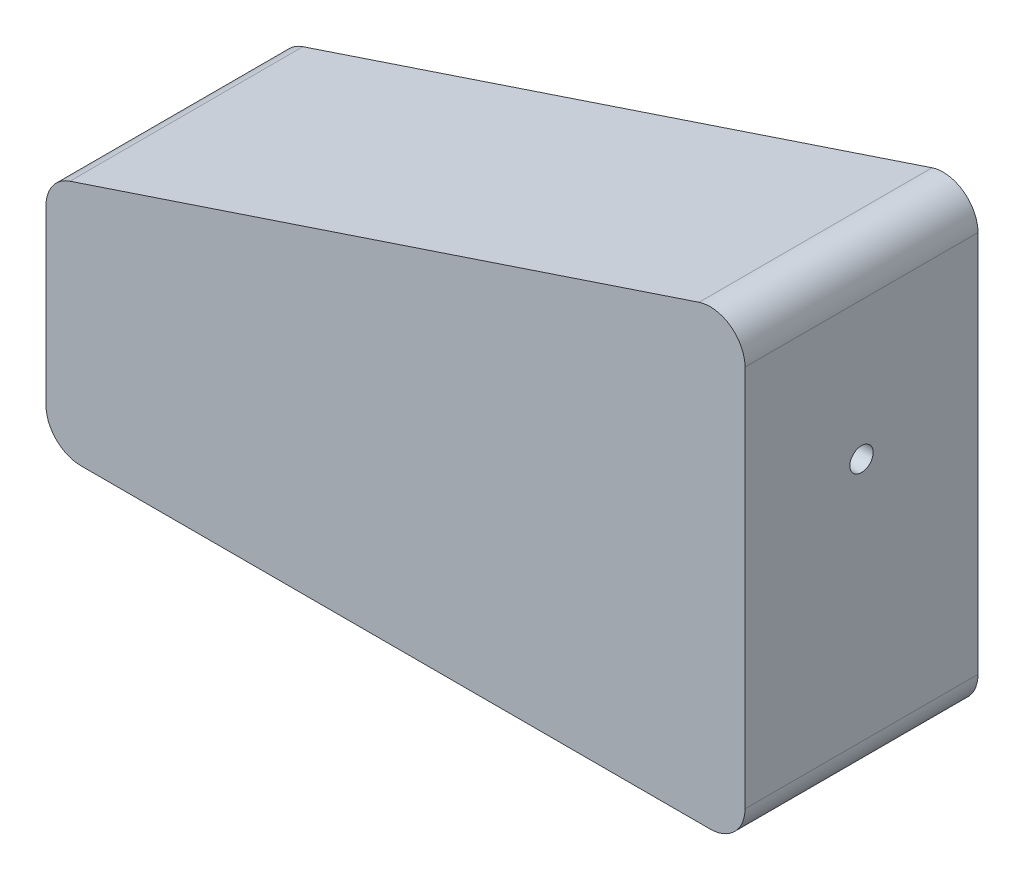
SolidWorks part; units mm, degrees
ref_plane "Plan de face" through (0, 0, 0) normal (0, 0, 1) x (1, 0, 0)
ref_plane "Plan de dessus" through (0, 0, 0) normal (0, 1, 0) x (1, 0, 0)
ref_plane "Plan de droite" through (0, 0, 0) normal (1, 0, 0) x (0, 0, -1)
sketch "Esquisse1" plane through (0, 0, 0) normal (0, 0, 1) x (1, 0, 0)
  line L0 (0, 0) -> (60, 0)
  line L1 (60, 0) -> (60, 40)
  line L2 (60, 40) -> (0, 20)
  line L3 (0, 20) -> (0, 0)
  dimension "D1" = 60
  dimension "D2" = 20
  dimension "D3" = 40
extrude "Boss.-Extru.1" add sketch "Esquisse1" along normal blind 20
fillet "Congé1" radius 3 4 edges at (0, 0, 10) (60, 0, 10) (60, 40, 10) (0, 20, 10)
sketch "Esquisse2" plane through (60, 0, 0) normal (1, 0, 0) x (0, 0, -1)
  line L0 (-10, 38.8377) -> (-10, 0) construction
  line L1 (0, 38.8377) -> (-20, 38.8377) construction
  line L2 (0, 0) -> (-20, 0) construction
  circle A0 centre (-10, 24) radius 1
  dimension "D1" = 24
  dimension "D2" = 2
extrude "Enlèv. mat.-Extru.1" cut sketch "Esquisse2" against normal blind 10
